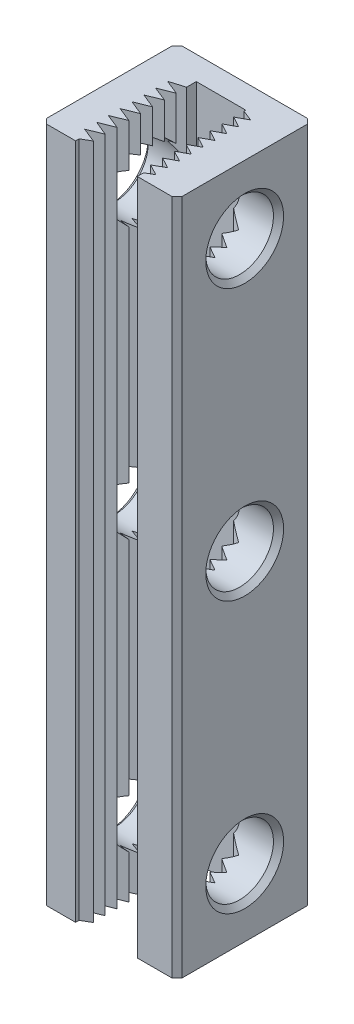
SolidWorks part; units mm, degrees
ref_plane "Front Plane" through (0, 0, 0) normal (0, 0, 1) x (1, 0, 0)
ref_plane "Top Plane" through (0, 0, 0) normal (0, 1, 0) x (1, 0, 0)
ref_plane "Right Plane" through (0, 0, 0) normal (1, 0, 0) x (0, 0, -1)
sketch "Sketch1" plane through (0, 0, 0) normal (0, 1, 0) x (1, 0, 0)
  line L1 (0, 0) -> (8, 0)
  line L2 (0, 0) -> (0, 8)
  line L3 (0, 8) -> (8, 8)
  line L4 (8, 0) -> (8, 8)
  dimension "D1" = 8
  dimension "D2" = 8
extrude "Boss-Extrude1" add sketch "Sketch1" along normal blind 300
sketch "Sketch2" plane through (0, 0, 0) normal (0, -1, 0) x (1, 0, 0)
  line L0 (5.652, 0) -> (2.0084, 0)
  line L1 (2.0084, 0) -> (2.0084, -0.2082)
  line L2 (2.0084, -0.2082) -> (2.54, -0.5151)
  line L3 (2.54, -0.5151) -> (1.6737, -0.8651)
  line L4 (1.6737, -0.8651) -> (2.54, -1.2151)
  line L5 (2.54, -1.2151) -> (1.6737, -1.5727)
  line L6 (1.6737, -1.5727) -> (2.54, -1.9151)
  line L7 (2.54, -1.9151) -> (1.6737, -2.2651)
  line L8 (1.6737, -2.2651) -> (2.54, -2.6151)
  line L9 (2.54, -2.6151) -> (1.6737, -2.9651)
  line L10 (1.6737, -2.9651) -> (2.54, -3.3151)
  line L11 (2.54, -3.3151) -> (1.6737, -3.6651)
  line L12 (1.6737, -3.6651) -> (2.54, -4.0151)
  line L13 (2.54, -4.0151) -> (1.6737, -4.3651)
  line L14 (1.6737, -4.3651) -> (2.54, -4.7151)
  line L15 (2.54, -4.7151) -> (1.6737, -5.0651)
  line L16 (1.6737, -5.0651) -> (2.54, -5.4151)
  line L17 (2.54, -5.4151) -> (1.6737, -5.7651)
  line L18 (1.6737, -5.7651) -> (2.54, -6.0264)
  line L19 (2.54, -6.0264) -> (2.54, -6.6)
  line L20 (2.54, -6.6) -> (5.46, -6.6)
  line L21 (5.46, -6.6) -> (5.46, -6.4988)
  line L22 (5.46, -6.4988) -> (6.1067, -6.2375)
  line L23 (6.1067, -6.2375) -> (5.46, -5.8875)
  line L24 (5.46, -5.8875) -> (6.1067, -5.5375)
  line L25 (6.1067, -5.5375) -> (5.46, -5.1875)
  line L26 (5.46, -5.1875) -> (6.1067, -4.8375)
  line L27 (6.1067, -4.8375) -> (5.46, -4.4875)
  line L28 (5.46, -4.4875) -> (6.1067, -4.1375)
  line L29 (6.1067, -4.1375) -> (5.46, -3.7875)
  line L30 (5.46, -3.7875) -> (6.1067, -3.4375)
  line L31 (6.1067, -3.4375) -> (5.46, -3.0875)
  line L32 (5.46, -3.0875) -> (6.1067, -2.7375)
  line L33 (6.1067, -2.7375) -> (5.46, -2.3875)
  line L34 (5.46, -2.3875) -> (6.1067, -2.0375)
  line L35 (6.1067, -2.0375) -> (5.46, -1.6875)
  line L36 (5.46, -1.6875) -> (6.1067, -1.3451)
  line L37 (6.1067, -1.3451) -> (5.46, -0.9875)
  line L38 (5.46, -0.9875) -> (6.1067, -0.6375)
  line L39 (6.1067, -0.6375) -> (5.652, -0.375)
  line L40 (5.652, -0.375) -> (5.652, 0)
  line L41 (0, -8) -> (0, 0) construction
  line L42 (8, -8) -> (0, -8) construction
  line L43 (0, 0) -> (8, 0) construction
  point P41 (0, 0)
  point P42 (0, 0)
  point P43 (0, 0)
  point P44 (0, 0)
  point P51 (0, 0)
  point P52 (0, 0)
  point P53 (4, -6.6)
  dimension "D1" = 2.92
  dimension "D2" = 0.8663
  dimension "D3" = 6.6
  dimension "D4" = 0.6467
  dimension "D5" = 4.433
  dimension "D6" = 4
extrude "Cut-Extrude1" cut sketch "Sketch2" against normal through all contours L0 L1 L2 L3 L4 L5 L6 L7 L8 L9 L10 L11 L12 L13 L14 L15 L16 L17 L18 L19 L20 L21 L22 L23 L24 L25 L26 L27 L28 L29 L30 L31 L32 L33 L34 L35 L36 L37 L38 L39 L40
sketch "Sketch3" plane through (8, 0, 0) normal (1, 0, 0) x (0, 0, -1)
  line L0 (0, 0) -> (8, 0) construction
  line L1 (8, 300) -> (8, 0) construction
  circle A0 centre (4, 4) radius 2
  dimension "D1" = 4
  dimension "D2" = 4
  dimension "D3" = 4
extrude "Cut-Extrude2" cut sketch "Sketch3" against normal through all
chamfer "Chamfer1" distance 0.3 angle 45 2 edges at (0, 4, -6) (8, 4, -6)
chamfer "Chamfer2" distance 0.3 angle 45 4 edges at (0, 150, -8) (0, 150, 0) (8, 150, -8) (8, 150, 0)
pattern_linear "LPattern1" count 19 spacing 16 along (0, 1, 0) of "Cut-Extrude2", "Chamfer1"
sketch "Sketch4" plane through (8, 0, 0) normal (1, 0, 0) x (0, 0, -1)
  line L0 (0.3, 300) -> (7.7, 300) construction
  line L1 (8, 300) -> (0, 300)
  line L2 (8, 300) -> (8, 40)
  line L3 (8, 40) -> (0, 40)
  line L4 (0, 300) -> (0, 40)
  line L5 (0, 0) -> (0, 300) construction
  line L6 (8, 300) -> (8, 0) construction
  line L7 (0.3, 0) -> (7.7, 0) construction
  point P7 (0, 0)
  dimension "D1" = 40
extrude "Cut-Extrude3" cut sketch "Sketch4" against normal through all
